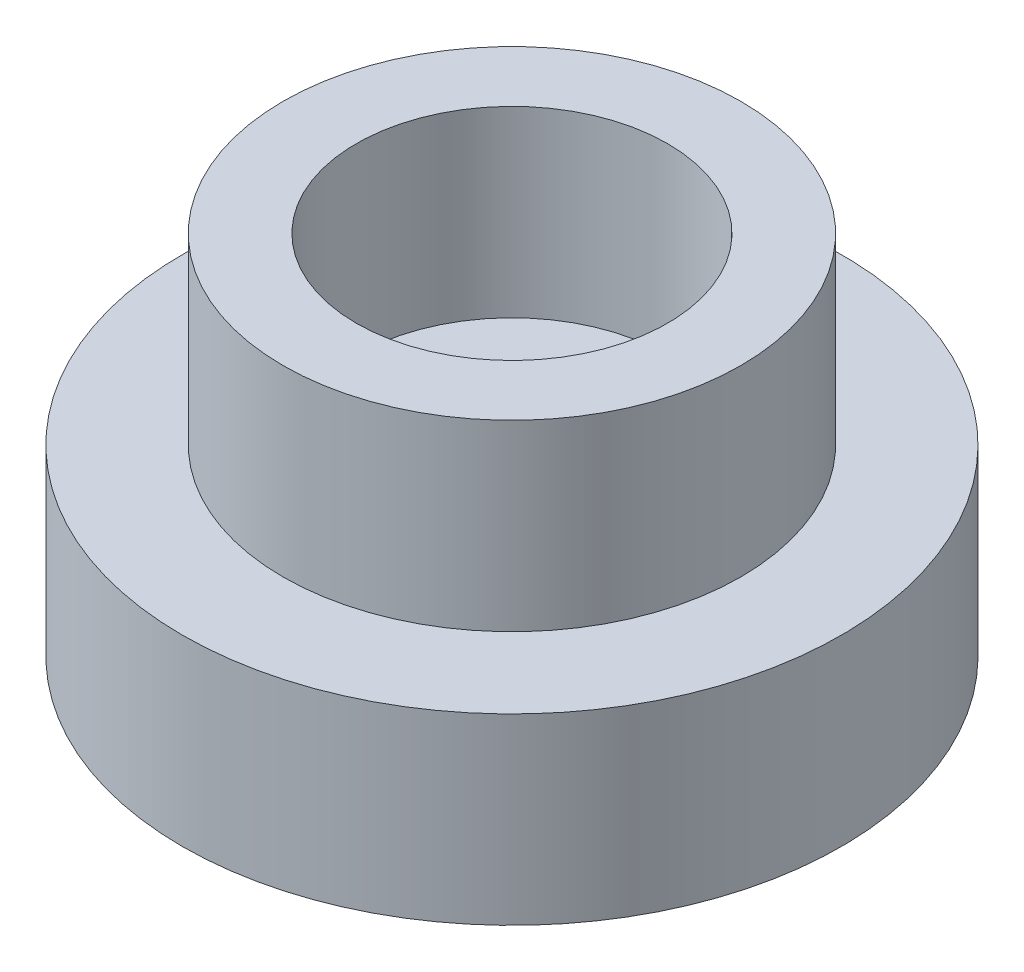
SolidWorks part; units mm, degrees
ref_plane "Front Plane" through (0, 0, 0) normal (0, 0, 1) x (1, 0, 0)
ref_plane "Top Plane" through (0, 0, 0) normal (0, 1, 0) x (1, 0, 0)
ref_plane "Right Plane" through (0, 0, 0) normal (1, 0, 0) x (0, 0, -1)
sketch "Sketch1" plane through (0, 0, 0) normal (0, 1, 0) x (1, 0, 0)
  circle A0 centre (0, 0) radius 9
  dimension "D1" = 18
extrude "Boss-Extrude1" add sketch "Sketch1" along normal blind 5
sketch "Sketch2" plane through (0, 5, 0) normal (0, 1, 0) x (1, 0, 0)
  circle A0 centre (0, 0) radius 6.25
  circle A1 centre (0, 0) radius 4.25
  dimension "D1" = 12.5
  dimension "D2" = 8.5
extrude "Boss-Extrude3" add sketch "Sketch2" along normal blind 5 contours A0 | A1
